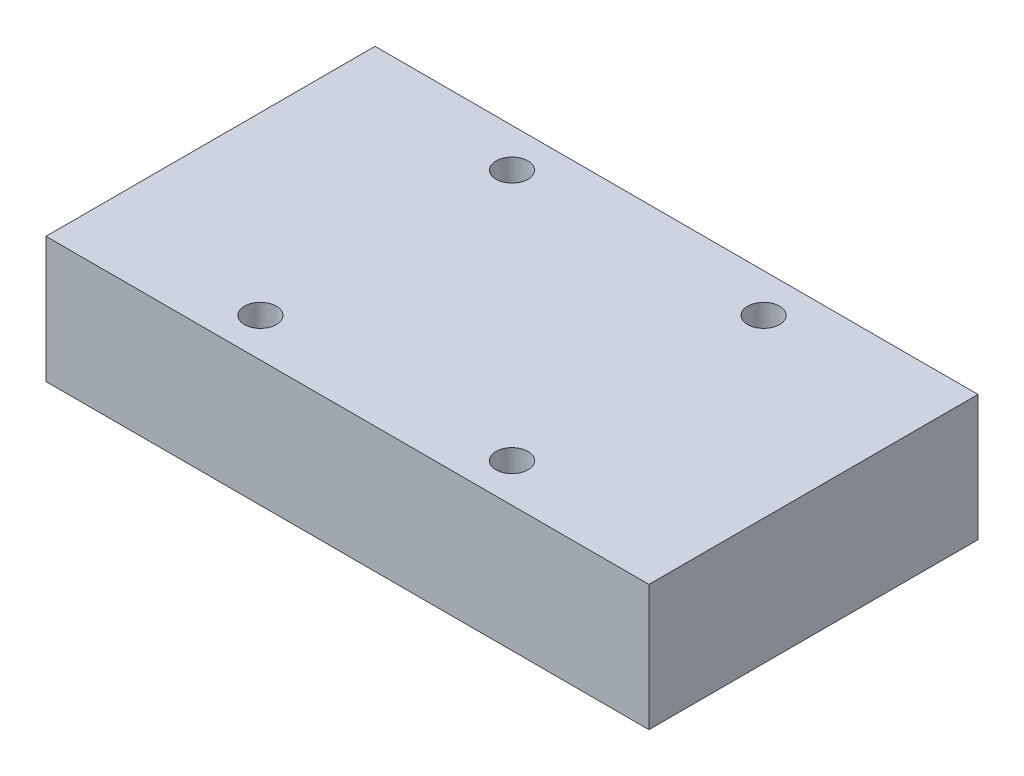
SolidWorks part; units mm, degrees
ref_plane "前视基准面" through (0, 0, 0) normal (0, 0, 1) x (1, 0, 0)
ref_plane "上视基准面" through (0, 0, 0) normal (0, 1, 0) x (1, 0, 0)
ref_plane "右视基准面" through (0, 0, 0) normal (1, 0, 0) x (0, 0, -1)
sketch "草图1" plane through (0, 0, 0) normal (0, 1, 0) x (1, 0, 0)
  line L1 (-31.15, 17) -> (31.15, 17)
  line L2 (-31.15, 17) -> (-31.15, -17)
  line L3 (-31.15, -17) -> (31.15, -17)
  line L4 (31.15, 17) -> (31.15, -17)
  line L5 (-31.15, 17) -> (31.15, -17) construction
  line L6 (-31.15, -17) -> (31.15, 17) construction
  point P0 (0, 0)
  dimension "D1" = 34
  dimension "D2" = 62.3
extrude "主体" add sketch "草图1" along normal blind 13
sketch "草图2" plane through (0, 13, 0) normal (0, 1, 0) x (1, 0, 0)
  line L1 (-13, 13) -> (13, 13) construction
  line L2 (-13, 13) -> (-13, -13) construction
  line L3 (-13, -13) -> (13, -13) construction
  line L4 (13, 13) -> (13, -13) construction
  line L5 (-13, 13) -> (13, -13) construction
  line L6 (-13, -13) -> (13, 13) construction
  point P0 (0, 0)
  dimension "D1" = 26
  dimension "D2" = 26
hole_wizard "M4 螺纹孔1" positions "草图5" profile "草图6" tap size "M4" standard "ISO"
sketch "草图5" plane through (0, 13, 0) normal (0, 1, 0) x (1, 0, 0)
  point P0 (-13, 13)
  point P2 (-13, -13)
  point P4 (13, 13)
  point P6 (13, -13)
sketch "草图6" plane through (-13, 13, -13) normal (1, 0, 0) x (0, 0, 1)
  line L0 (0, 0) -> (0, 5.9914)
  line L1 (0, 5.9914) -> (1.65, 5)
  line L2 (1.65, 5) -> (1.65, 0)
  line L5 (1.65, 0) -> (0, 0)
  line L10 (0, 5.9914) -> (-1.65, 5) construction
  line L11 (0, -6.35) -> (0, 107.95) construction
  dimension "螺纹孔钻头直径" = 3.3
  dimension "螺纹孔钻头深度" = 5
  dimension "导头角度" = 118
cosmetic thread "孔螺蚊线5" parameters "D1"=5, "D2"=4
cosmetic thread "孔螺蚊线6" parameters "D1"=5, "D2"=4
cosmetic thread "孔螺蚊线7" parameters "D1"=5, "D2"=4
cosmetic thread "孔螺蚊线8" parameters "D1"=5, "D2"=4
